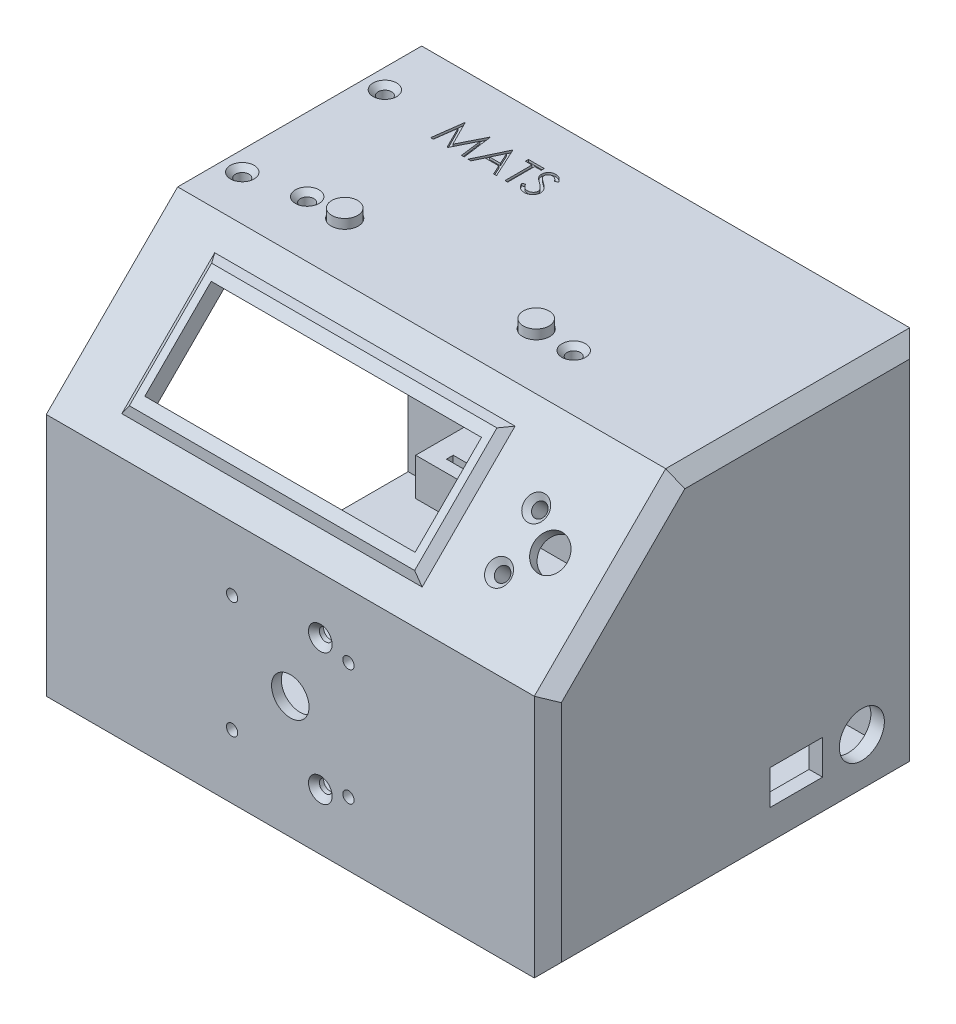
SolidWorks part; units mm, degrees
ref_plane "Front Plane" through (0, 0, 0) normal (0, 0, 1) x (1, 0, 0)
ref_plane "Top Plane" through (0, 0, 0) normal (0, 1, 0) x (1, 0, 0)
ref_plane "Right Plane" through (0, 0, 0) normal (1, 0, 0) x (0, 0, -1)
sketch "Sketch1" plane through (0, 0, 0) normal (0, 0, 1) x (1, 0, 0)
  line L1 (-65, 32.5) -> (65, 32.5)
  line L2 (-65, 32.5) -> (-65, -32.5)
  line L3 (-65, -32.5) -> (65, -32.5)
  line L4 (65, 32.5) -> (65, -32.5)
  line L5 (-65, 32.5) -> (65, -32.5) construction
  line L6 (-65, -32.5) -> (65, 32.5) construction
  point P0 (0, 0)
  dimension "D1" = 130
  dimension "D2" = 65
extrude "Boss-Extrude1" add sketch "Sketch1" against normal blind 3.6 contours L2 L3 L4 L1
sketch "Sketch2" plane through (65, 0, 0) normal (1, 0, 0) x (0, 0, -1)
  line L0 (0, -32.5) -> (100, -32.5)
  line L1 (100, -32.5) -> (100, 67.5)
  line L2 (100, 67.5) -> (35, 67.5)
  line L3 (35, 67.5) -> (0, 32.5)
  line L4 (0, 32.5) -> (0, -32.5)
  dimension "D1" = 135
  dimension "D2" = 65
  dimension "D3" = 100
ref_plane "Plane1" through (0, 16.25, 16.25) normal (0, -0.7071, -0.7071) x (-1, 0, 0)
sketch "Sketch5" plane through (0, 16.25, 16.25) normal (0, -0.7071, -0.7071) x (-1, 0, 0)
  line L1 (65, 22.981) -> (-65, 22.981)
  line L2 (65, 22.981) -> (65, 72.4784)
  line L3 (65, 72.4784) -> (-65, 72.4784)
  line L4 (-65, 22.981) -> (-65, 72.4784)
extrude "Boss-Extrude2" add sketch "Sketch5" along normal blind 2.8
ref_plane "Plane2" through (0, 67.5, 0) normal (0, -1, 0) x (-1, 0, 0)
sketch "Sketch7" plane through (0, 67.5, 0) normal (0, -1, 0) x (-1, 0, 0)
  line L1 (65, 35) -> (-65, 35)
  line L2 (65, 35) -> (65, 100)
  line L3 (65, 100) -> (-65, 100)
  line L4 (-65, 35) -> (-65, 100)
extrude "Boss-Extrude3" add sketch "Sketch7" along normal blind 3.6
ref_plane "Plane3" through (0, -32.5, 0) normal (0, 1, 0) x (1, 0, 0)
ref_plane "Plane4" through (0, 0, -100) normal (0, 0, -1) x (-1, 0, 0)
sketch "Sketch9" plane through (0, -32.5, 0) normal (0, 1, 0) x (1, 0, 0)
  line L1 (65, 0) -> (-65, 0)
  line L2 (65, 0) -> (65, 100)
  line L3 (65, 100) -> (-65, 100)
  line L4 (-65, 0) -> (-65, 100)
  line L6 (65, 100) -> (65, 35) construction
extrude "Boss-Extrude4" add sketch "Sketch9" along normal blind 3.6
sketch "Sketch10" plane through (0, 0, -100) normal (0, 0, -1) x (-1, 0, 0)
  line L1 (-65, 67.5) -> (65, 67.5)
  line L2 (-65, 67.5) -> (-65, -32.5)
  line L3 (-65, -32.5) -> (65, -32.5)
  line L4 (65, 67.5) -> (65, -32.5)
extrude "Boss-Extrude5" add sketch "Sketch10" against normal blind 3.6
extrude "Boss-Extrude6" add sketch "Sketch2" along normal blind 3.6 draft 45
sketch "Sketch11" plane through (0, 16.25, 16.25) normal (0, 0.7071, 0.7071) x (1, 0, 0)
  line L0 (-65, 22.981) -> (-65, 72.4784) construction
  line L1 (-50, 65.2297) -> (30, 65.2297)
  line L2 (-50, 65.2297) -> (-50, 30.2297)
  line L3 (-50, 30.2297) -> (30, 30.2297)
  line L4 (30, 65.2297) -> (30, 30.2297)
  point P4 (-50, 47.7297)
  dimension "D1" = 80
  dimension "D2" = 35
  dimension "D3" = 15
extrude "Boss-Extrude7" add sketch "Sketch11" along normal blind 2 draft 45
sketch "Sketch12" plane through (0, 17.6642, 17.6642) normal (0, 0.7071, 0.7071) x (1, 0, 0)
  line L1 (-46, 35.2297) -> (26, 35.2297)
  line L2 (-46, 35.2297) -> (-46, 60.2297)
  line L3 (-46, 60.2297) -> (26, 60.2297)
  line L4 (26, 35.2297) -> (26, 60.2297)
  line L5 (-46, 35.2297) -> (26, 60.2297) construction
  line L6 (-46, 60.2297) -> (26, 35.2297) construction
  line L7 (28, 63.2297) -> (-48, 32.2297) construction
  point P0 (-10, 47.7297)
  point P9 (-10, 47.7297)
  dimension "D1" = 72
  dimension "D2" = 25
extrude "Cut-Extrude1" cut sketch "Sketch12" against normal up to next
sketch "Sketch13" plane through (65, 0, 0) normal (-1, 0, 0) x (0, 0, 1)
  line L1 (-73.186, -20.9627) -> (-59.186, -20.9627)
  line L2 (-73.186, -20.9627) -> (-73.186, -11.7627)
  line L3 (-73.186, -11.7627) -> (-59.186, -11.7627)
  line L4 (-59.186, -20.9627) -> (-59.186, -11.7627)
  line L5 (-73.186, -20.9627) -> (-59.186, -11.7627) construction
  line L6 (-73.186, -11.7627) -> (-59.186, -20.9627) construction
  circle A0 centre (-83.6497, -16.3627) radius 6
  point P0 (-66.186, -16.3627)
  dimension "D3" = 6
  dimension "D1" = 14
  dimension "D2" = 9.2
extrude "Cut-Extrude2" cut sketch "Sketch13" against normal up to next
sketch "Sketch14" plane through (0, 14.2701, 14.2701) normal (0, -0.7071, -0.7071) x (1, 0, 0)
  line L1 (27, -70.1873) -> (37, -70.1873)
  line L2 (27, -70.1873) -> (27, -25.2721)
  line L3 (27, -25.2721) -> (37, -25.2721)
  line L4 (37, -70.1873) -> (37, -25.2721)
  line L5 (65, -25.2721) -> (-65, -25.2721) construction
  line L6 (26, -35.2297) -> (26, -60.2297) construction
  dimension "D1" = 10
  dimension "D2" = 1
ref_plane "Plane5" through (0, 10.0275, 10.0275) normal (0, -0.7071, -0.7071) x (-1, 0, 0)
sketch "Sketch15" plane through (0, 10.0275, 10.0275) normal (0, -0.7071, -0.7071) x (-1, 0, 0)
  line L0 (-27, 70.1873) -> (-27, 25.2721) construction
  line L1 (-27, 79.3357) -> (-35, 79.3357)
  line L2 (-27, 79.3357) -> (-27, 14.3733)
  line L3 (-27, 14.3733) -> (-35, 14.3733)
  line L4 (-35, 79.3357) -> (-35, 14.3733)
  dimension "D1" = 8
loft "Loft1" add profiles "Sketch15", "Sketch14"
sketch "Sketch16" plane through (27, 0, 0) normal (-1, 0, 0) x (0, 0, 1)
  line L0 (-14.9903, 43.5305) -> (-25.5969, 54.1371)
  line L1 (-3.6, 32.1402) -> (-35.3598, 63.9) construction
  line L2 (-25.5969, 54.1371) -> (-27.1526, 52.5815)
  line L3 (-27.1526, 52.5815) -> (-34.754, 60.1829)
  line L4 (-34.754, 60.1829) -> (-36.1682, 58.7687)
  line L5 (-36.1682, 58.7687) -> (-9.581, 32.1815)
  line L6 (-9.581, 32.1815) -> (-8.1667, 33.5957)
  line L7 (-8.1667, 33.5957) -> (-16.546, 41.9749)
  line L8 (-16.546, 41.9749) -> (-14.9903, 43.5305)
  point P5 (-20.2936, 48.8338)
  dimension "D1" = 37.6
  dimension "D2" = 15
  dimension "D3" = 2.2
  dimension "D4" = 2
extrude "Cut-Extrude3" cut sketch "Sketch16" against normal blind 5
sketch "Sketch17" plane through (0, 0, 0) normal (0, 0, 1) x (1, 0, 0)
  circle A0 centre (0, 0) radius 5
  dimension "D1" = 5
extrude "Cut-Extrude4" cut sketch "Sketch17" against normal up to next
sketch "Sketch18" plane through (0, 0, 0) normal (0, 0, 1) x (1, 0, 0)
  line L0 (8, 17.5) -> (8, -17.5) construction
  point P3 (8, 0)
  dimension "D1" = 8
  dimension "D2" = 35
hole_wizard "CSK for M3 Countersunk Flat Head1" positions "Sketch19" profile "Sketch20" countersink size "M3" standard "BSI"
sketch "Sketch19" plane through (0, 0, 0) normal (0, 0, 1) x (1, 0, 0)
  point P0 (8, 17.5)
  point P3 (8, -17.5)
sketch "Sketch20" plane through (8, 17.5, 0) normal (1, 0, 0) x (0, -1, 0)
  line L0 (0, 0) -> (0, 3.6)
  line L1 (0, 3.6) -> (1.7, 3.6)
  line L2 (1.7, 3.6) -> (1.7, 1.45)
  line L3 (1.7, 1.45) -> (3.15, 0)
  line L5 (3.15, 0) -> (0, 0)
  line L6 (-1.7, 1.45) -> (-3.15, 0) construction
  line L11 (0, -6.35) -> (0, 107.95) construction
  dimension "Thru Hole Dia." = 3.4
  dimension "Thru Hole Depth" = 3.6
  dimension "Near C'Sink Dia." = 6.3
  dimension "Near C'Sink Angle" = 90
sketch "Sketch21" plane through (0, 0, -3.6) normal (0, 0, -1) x (-1, 0, 0)
  line L0 (-8, 17.5) -> (-8, -17.5) construction
  line L1 (-8, 17.5) -> (-8, -17.5) construction
  line L2 (-4.1758, -13.6234) -> (-4.25, -17.5)
  line L3 (-11.75, 17.5) -> (-11.7477, 13.6447)
  line L4 (-4.25, 17.5) -> (-4.25, 13.644)
  line L5 (-11.75, -17.5) -> (-11.75, -13.644)
  line L6 (-20.8149, 6) -> (-26, 6)
  line L7 (-26, 6) -> (-26, -6)
  line L8 (-26, -6) -> (-20.8149, -6)
  arc A0 (-11.7477, 13.6447) -> (-20.8149, 6) centre (-8, 0) ccw
  arc A1 (-4.25, 17.5) -> (-11.75, 17.5) centre (-8, 17.5) ccw
  arc A2 (-11.75, -17.5) -> (-4.25, -17.5) centre (-8, -17.5) ccw
  arc A3 (-4.1758, -13.6234) -> (-4.25, 13.644) centre (-8, 0) ccw
  arc A4 (-20.8149, -6) -> (-11.75, -13.644) centre (-8, 0) ccw
  point P8 (-8, 0)
  point P17 (-26, 0)
  dimension "D1" = 14.15
  dimension "D2" = 12
  dimension "D3" = 18
sketch "Sketch22" plane through (65, 0, 0) normal (-1, 0, 0) x (0, 0, 1)
  line L0 (-63.6165, 21.8931) -> (-63.6165, -4.6069) construction
  line L1 (-63.6165, -4.6069) -> (-34.1165, -4.6069) construction
  line L2 (-34.1165, -4.6069) -> (-34.1165, 21.8931) construction
  line L3 (-34.1165, 21.8931) -> (-63.6165, 21.8931) construction
  line L5 (-68.6165, 26.8931) -> (-58.6165, 26.8931)
  line L6 (-68.6165, 26.8931) -> (-68.6165, 16.8931)
  line L7 (-68.6165, 16.8931) -> (-58.6165, 16.8931)
  line L8 (-58.6165, 26.8931) -> (-58.6165, 16.8931)
  line L9 (-68.6165, 26.8931) -> (-58.6165, 16.8931) construction
  line L10 (-68.6165, 16.8931) -> (-58.6165, 26.8931) construction
  line L11 (-39.1165, 26.8931) -> (-29.1165, 26.8931)
  line L12 (-39.1165, 26.8931) -> (-39.1165, 16.8931)
  line L13 (-39.1165, 16.8931) -> (-29.1165, 16.8931)
  line L14 (-29.1165, 26.8931) -> (-29.1165, 16.8931)
  line L15 (-39.1165, 26.8931) -> (-29.1165, 16.8931) construction
  line L16 (-39.1165, 16.8931) -> (-29.1165, 26.8931) construction
  line L17 (-68.6165, -9.6069) -> (-58.6165, -9.6069)
  line L18 (-68.6165, -9.6069) -> (-68.6165, 0.3931)
  line L19 (-68.6165, 0.3931) -> (-58.6165, 0.3931)
  line L20 (-58.6165, -9.6069) -> (-58.6165, 0.3931)
  line L21 (-68.6165, -9.6069) -> (-58.6165, 0.3931) construction
  line L22 (-68.6165, 0.3931) -> (-58.6165, -9.6069) construction
  line L23 (-39.1165, 0.3931) -> (-29.1165, 0.3931)
  line L24 (-39.1165, 0.3931) -> (-39.1165, -9.6069)
  line L25 (-39.1165, -9.6069) -> (-29.1165, -9.6069)
  line L26 (-29.1165, 0.3931) -> (-29.1165, -9.6069)
  line L27 (-39.1165, 0.3931) -> (-29.1165, -9.6069) construction
  line L28 (-39.1165, -9.6069) -> (-29.1165, 0.3931) construction
  dimension "D1" = 29.5
  dimension "D2" = 26.5
  dimension "D3" = 10
extrude "Boss-Extrude8" add sketch "Sketch22" along normal blind 8
sketch "Sketch23" plane through (65, 0, 0) normal (-1, 0, 0) x (0, 0, 1)
  line L0 (-66.6165, 26.8931) -> (-66.6165, 20.4251)
  line L1 (-66.6165, 20.4251) -> (-63.6165, 18.6931)
  line L2 (-63.6165, 21.8931) -> (-63.6165, -4.6069) construction
  line L3 (-63.6165, 18.6931) -> (-60.6165, 20.4251)
  line L4 (-39.1165, 0.3931) -> (-29.1165, 0.3931) construction
  line L5 (-60.6165, 20.4251) -> (-60.6165, 26.8931)
  line L6 (-60.6165, 26.8931) -> (-66.6165, 26.8931)
  line L7 (-68.6165, 0.3931) -> (-58.6165, 0.3931) construction
  line L8 (-68.6165, 26.8931) -> (-58.6165, 26.8931) construction
  line L9 (-34.1165, -4.6069) -> (-34.1165, 21.8931) construction
  line L10 (-37.1165, 26.8931) -> (-37.1165, 20.4251)
  line L11 (-37.1165, 20.4251) -> (-34.1165, 18.6931)
  line L12 (-34.1165, 18.6931) -> (-31.1165, 20.4251)
  line L13 (-31.1165, 20.4251) -> (-31.1165, 26.8931)
  line L14 (-31.1165, 26.8931) -> (-37.1165, 26.8931)
  line L15 (-66.6165, 0.3931) -> (-66.6165, -6.0749)
  line L16 (-66.6165, -6.0749) -> (-63.6165, -7.8069)
  line L17 (-63.6165, -7.8069) -> (-60.6165, -6.0749)
  line L18 (-60.6165, -6.0749) -> (-60.6165, 0.3931)
  line L19 (-60.6165, 0.3931) -> (-66.6165, 0.3931)
  line L20 (-37.1165, 0.3931) -> (-37.1165, -6.0749)
  line L21 (-37.1165, -6.0749) -> (-34.1165, -7.8069)
  line L22 (-34.1165, -7.8069) -> (-31.1165, -6.0749)
  line L23 (-31.1165, -6.0749) -> (-31.1165, 0.3931)
  line L24 (-31.1165, 0.3931) -> (-37.1165, 0.3931)
  line L25 (-39.1165, 26.8931) -> (-29.1165, 26.8931) construction
  dimension "D1" = 6
  dimension "D2" = 120
  dimension "D3" = 120
  dimension "D4" = 8.2
  dimension "D5" = 6
  dimension "D6" = 120
  dimension "D7" = 120
  dimension "D8" = 6
  dimension "D9" = 120
  dimension "D10" = 120
  dimension "D11" = 6
  dimension "D12" = 120
  dimension "D13" = 120
  dimension "D14" = 8.2
  dimension "D15" = 8.2
  dimension "D16" = 10
  dimension "D17" = 10
  dimension "D18" = 8.2
extrude "Cut-Extrude5" cut sketch "Sketch23" along normal blind 3
hole_wizard "Ø3.0mm Dowel Hole1" positions "Sketch24" profile "Sketch26" hole size "Ø3.0" standard "BSI"
sketch "Sketch24" plane through (57, 0, 0) normal (-1, 0, 0) x (0, 0, 1)
  point P0 (-63.6165, 21.8931)
  point P3 (-34.1165, 21.8931)
  point P6 (-63.6165, -4.6069)
  point P9 (-34.1165, -4.6069)
sketch "Sketch26" plane through (57, 21.8931, -63.6165) normal (0, 1, 0) x (0, 0, 1)
  line L0 (0, 0) -> (0, 8.9003)
  line L1 (0, 8.9003) -> (1.5, 7.999)
  line L2 (1.5, 7.999) -> (1.5, 0)
  line L5 (1.5, 0) -> (0, 0)
  line L10 (0, 8.9003) -> (-1.5, 7.999) construction
  line L11 (0, -6.35) -> (0, 107.95) construction
  dimension "Hole Dia." = 3
  dimension "Hole Depth" = 7.999
  dimension "Drill Angle" = 118
sketch "Sketch27" plane through (0, 0, -96.4) normal (0, 0, 1) x (1, 0, 0)
  line L0 (-45, 53.9) -> (35, 53.9) construction
  line L1 (35, 53.9) -> (35, -16.1) construction
  line L2 (35, -16.1) -> (-45, -16.1) construction
  line L3 (-45, -16.1) -> (-45, 53.9) construction
  line L4 (-65, -28.9) -> (-65, 63.9) construction
  line L5 (-65, 63.9) -> (65, 63.9) construction
  line L7 (-50, -11.1) -> (-30, -11.1)
  line L8 (-50, -11.1) -> (-50, -21.1)
  line L9 (-50, -21.1) -> (-30, -21.1)
  line L10 (-30, -11.1) -> (-30, -21.1)
  line L11 (-50, -11.1) -> (-30, -21.1) construction
  line L12 (-50, -21.1) -> (-30, -11.1) construction
  line L13 (20, -11.1) -> (40, -11.1)
  line L14 (20, -11.1) -> (20, -21.1)
  line L15 (20, -21.1) -> (40, -21.1)
  line L16 (40, -11.1) -> (40, -21.1)
  line L17 (20, -11.1) -> (40, -21.1) construction
  line L18 (20, -21.1) -> (40, -11.1) construction
  point P8 (-40, -16.1)
  point P13 (30, -16.1)
  dimension "D1" = 80
  dimension "D2" = 70
  dimension "D3" = 20
  dimension "D4" = 10
  dimension "D5" = 5
  dimension "D6" = 10
  dimension "D7" = 20
  dimension "D8" = 5
  dimension "D9" = 10
  dimension "D10" = 20
extrude "Boss-Extrude9" add sketch "Sketch27" along normal blind 13
sketch "Sketch28" plane through (0, -11.1, 0) normal (0, 1, 0) x (1, 0, 0)
  line L1 (-30, 88.4) -> (-45, 88.4)
  line L2 (-30, 88.4) -> (-30, 86.5985)
  line L3 (-30, 86.5985) -> (-45, 86.5985)
  line L4 (-45, 88.4) -> (-45, 86.5985)
  line L6 (20, 88.4) -> (35, 88.4)
  line L7 (20, 88.4) -> (20, 86.5985)
  line L8 (20, 86.5985) -> (35, 86.5985)
  line L9 (35, 88.4) -> (35, 86.5985)
  line L11 (-50, 96.4) -> (-30, 96.4) construction
  dimension "D1" = 15
  dimension "D2" = 1.8015
  dimension "D3" = 8
extrude "Cut-Extrude12" cut sketch "Sketch28" against normal blind 5
sketch "Sketch29" plane through (0, 0, -96.4) normal (0, 0, 1) x (1, 0, 0)
  line L0 (-45, -16.1) -> (-45, 53.9) construction
  line L1 (35, 53.9) -> (35, -16.1) construction
  line L2 (-45, 53.9) -> (35, 53.9) construction
  line L3 (-30, 48.9) -> (-30, 32.8454) construction
  line L4 (1, 48.9) -> (-30, 48.9) construction
  line L5 (-35, 53.9) -> (-25, 53.9)
  line L6 (-35, 53.9) -> (-35, 43.9)
  line L7 (-35, 43.9) -> (-25, 43.9)
  line L8 (-25, 53.9) -> (-25, 43.9)
  line L9 (-35, 53.9) -> (-25, 43.9) construction
  line L10 (-35, 43.9) -> (-25, 53.9) construction
  line L11 (20, 48.9) -> (20, 33.3075) construction
  line L12 (51, 48.9) -> (20, 48.9) construction
  line L13 (15, 53.9) -> (25, 53.9)
  line L14 (15, 53.9) -> (15, 43.9)
  line L15 (15, 43.9) -> (25, 43.9)
  line L16 (25, 53.9) -> (25, 43.9)
  line L17 (15, 53.9) -> (25, 43.9) construction
  line L18 (15, 43.9) -> (25, 53.9) construction
  point P0 (-30, 48.9)
  point P1 (20, 48.9)
  dimension "D1" = 15
  dimension "15" = 15
  dimension "D2" = 5
  dimension "D3" = 31
  dimension "D4" = 10
  dimension "D5" = 31
  dimension "D6" = 10
extrude "Boss-Extrude10" add sketch "Sketch29" along normal blind 8
ref_plane "Plane6" through (0, 0, -94.4) normal (0, 0, 1) x (1, 0, 0)
sketch "Sketch31" plane through (0, 0, -94.4) normal (0, 0, 1) x (1, 0, 0)
  line L0 (-33, 53.9) -> (-33, 47.432)
  line L1 (-33, 47.432) -> (-30, 45.6999)
  line L2 (-30, 45.6999) -> (-27, 47.432)
  line L3 (-27, 47.432) -> (-27, 53.9)
  line L4 (-27, 53.9) -> (-33, 53.9)
  line L5 (-35, 53.9) -> (-25, 53.9) construction
  line L6 (-30, 48.9) -> (-30, 32.8454) construction
  line L7 (17, 53.9) -> (17, 47.4321)
  line L8 (17, 47.4321) -> (20, 45.7)
  line L9 (20, 45.7) -> (23, 47.4321)
  line L10 (23, 47.4321) -> (23, 53.9)
  line L11 (23, 53.9) -> (17, 53.9)
  line L12 (20, 48.9) -> (20, 33.3075) construction
  line L13 (15, 53.9) -> (25, 53.9) construction
  dimension "D1" = 6
  dimension "D2" = 120
  dimension "D3" = 120
  dimension "D4" = 3.2001
  dimension "D5" = 6
  dimension "D6" = 120
  dimension "D7" = 120
  dimension "D8" = 3.2
extrude "Cut-Extrude7" cut sketch "Sketch31" along normal blind 3
hole_wizard "Ø5.0mm Dowel Hole1" positions "Sketch34" profile "Sketch33" hole size "Ø5.0" standard "BSI"
sketch "Sketch34" plane through (0, 0, -88.4) normal (0, 0, 1) x (1, 0, 0)
  point P0 (-30, 48.9)
  point P3 (20, 48.9)
sketch "Sketch33" plane through (-30, 48.9, -88.4) normal (1, 0, 0) x (0, -1, 0)
  line L0 (0, 0) -> (0, 10.5022)
  line L1 (0, 10.5022) -> (2.5, 9)
  line L2 (2.5, 9) -> (2.5, 0)
  line L5 (2.5, 0) -> (0, 0)
  line L10 (0, 10.5022) -> (-2.5, 9) construction
  line L11 (0, -6.35) -> (0, 107.95) construction
  dimension "Hole Dia." = 5
  dimension "Hole Depth" = 9
  dimension "Drill Angle" = 118
sketch "Sketch35" plane through (0, 0, 0) normal (0, 0, 1) x (1, 0, 0)
  line L0 (-15.5, 15.5) -> (15.5, -15.5) construction
  line L1 (15.5, 15.5) -> (-15.5, -15.5) construction
  point P2 (0, 0)
  point P7 (0, 0)
  dimension "D1" = 31
hole_wizard "Ø3.0mm Dowel Hole3" positions "Sketch36" profile "Sketch38" hole size "Ø3.0" standard "BSI" end condition up to next
sketch "Sketch36" plane through (0, 0, 0) normal (0, 0, 1) x (1, 0, 0)
  point P0 (-15.5, 15.5)
  point P3 (15.5, 15.5)
  point P6 (15.5, -15.5)
  point P9 (-15.5, -15.5)
sketch "Sketch38" plane through (-15.5, 15.5, 0) normal (1, 0, 0) x (0, -1, 0)
  line L0 (0, 0) -> (0, 3.6)
  line L1 (0, 3.6) -> (1.5, 3.6)
  line L2 (1.5, 3.6) -> (1.5, 0)
  line L5 (1.5, 0) -> (0, 0)
  line L11 (0, -6.35) -> (0, 107.95) construction
  dimension "Thru Hole Dia." = 3
  dimension "Thru Hole Depth" = 3.6
sketch "Sketch39" plane through (0, 0, -3.6) normal (0, 0, -1) x (-1, 0, 0)
  line L1 (-12.5004, 13.7673) -> (-12.4996, 17.2314)
  line L2 (-12.4996, 17.2314) -> (-15.4993, 18.9641)
  line L3 (-15.4993, 18.9641) -> (-18.4996, 17.2327)
  line L4 (-18.4996, 17.2327) -> (-18.5004, 13.7686)
  line L5 (-18.5004, 13.7686) -> (-15.5007, 12.0359)
  line L6 (-15.5007, 12.0359) -> (-12.5004, 13.7673)
  line L12 (18.6392, 13.9759) -> (18.6399, 17.44)
  line L13 (18.6399, 17.44) -> (15.6402, 19.1727)
  line L14 (15.6402, 19.1727) -> (12.6399, 17.4413)
  line L15 (12.6399, 17.4413) -> (12.6392, 13.9771)
  line L16 (12.6392, 13.9771) -> (15.6388, 12.2445)
  line L17 (15.6388, 12.2445) -> (18.6392, 13.9759)
  line L18 (-12.7838, -16.9883) -> (-12.7831, -13.5242)
  line L19 (-12.7831, -13.5242) -> (-15.7827, -11.7915)
  line L20 (-15.7827, -11.7915) -> (-18.7831, -13.523)
  line L21 (-18.7831, -13.523) -> (-18.7838, -16.9871)
  line L22 (-18.7838, -16.9871) -> (-15.7841, -18.7197)
  line L23 (-15.7841, -18.7197) -> (-12.7838, -16.9883)
  line L24 (18.62, -16.9023) -> (18.6207, -13.4382)
  line L25 (18.6207, -13.4382) -> (15.621, -11.7055)
  line L26 (15.621, -11.7055) -> (12.6207, -13.4369)
  line L27 (12.6207, -13.4369) -> (12.62, -16.901)
  line L28 (12.62, -16.901) -> (15.6196, -18.6337)
  line L29 (15.6196, -18.6337) -> (18.62, -16.9023)
  circle A0 centre (-15.5, 15.5) radius 3 construction
  circle A1 centre (15.6395, 15.7086) radius 3 construction
  circle A2 centre (-15.7834, -15.2556) radius 3 construction
  circle A3 centre (15.6203, -15.1696) radius 3 construction
extrude "Cut-Extrude8" cut sketch "Sketch39" against normal blind 1.5
hole_wizard "CSK for M3 Countersunk Flat Head4" positions "Sketch48" profile "Sketch49" countersink size "M3" standard "BSI" end condition up to next
sketch "Sketch48" plane through (0, -32.5, 0) normal (0, -1, 0) x (-1, 0, 0)
  point P0 (59.8, 25)
  point P2 (59.8, 75)
sketch "Sketch49" plane through (-59.8, -32.5, -25) normal (1, 0, 0) x (0, 0, -1)
  line L0 (0, 0) -> (0, 3.6)
  line L1 (0, 3.6) -> (1.8, 3.6)
  line L2 (1.8, 3.6) -> (1.8, 1.35)
  line L3 (1.8, 1.35) -> (3.15, 0)
  line L5 (3.15, 0) -> (0, 0)
  line L6 (-1.8, 1.35) -> (-3.15, 0) construction
  line L11 (0, -6.35) -> (0, 107.95) construction
  dimension "Thru Hole Dia." = 3.6
  dimension "Thru Hole Depth" = 3.6
  dimension "Near C'Sink Dia." = 6.3
  dimension "Near C'Sink Angle" = 90
hole_wizard "CSK for M3 Countersunk Flat Head5" positions "Sketch52" profile "Sketch54" countersink size "M3" standard "BSI" end condition up to next
sketch "Sketch52" plane through (0, 67.5, 0) normal (0, 1, 0) x (1, 0, 0)
  line L0 (-65, 35) -> (65, 35) construction
  line L1 (-65, 35) -> (-65, 100) construction
  line L2 (-65, 100) -> (65, 100) construction
  point P0 (-59.8, 85)
  point P2 (-59.8, 47)
  dimension "D1" = 12
  dimension "D2" = 5.2
  dimension "D3" = 15
  dimension "D4" = 5.2
sketch "Sketch54" plane through (-59.8, 67.5, -85) normal (1, 0, 0) x (0, 0, 1)
  line L0 (0, 0) -> (0, 3.6)
  line L1 (0, 3.6) -> (1.8, 3.6)
  line L2 (1.8, 3.6) -> (1.8, 1.35)
  line L3 (1.8, 1.35) -> (3.15, 0)
  line L5 (3.15, 0) -> (0, 0)
  line L6 (-1.8, 1.35) -> (-3.15, 0) construction
  line L11 (0, -6.35) -> (0, 107.95) construction
  dimension "Thru Hole Dia." = 3.6
  dimension "Thru Hole Depth" = 3.6
  dimension "Near C'Sink Dia." = 6.3
  dimension "Near C'Sink Angle" = 90
sketch "Sketch55" plane through (0, 63.9, 0) normal (0, -1, 0) x (1, 0, 0)
  line L0 (-35.5, -50) -> (15.5, -50) construction
  line L4 (-65, -35) -> (65, -35) construction
  line L6 (-42.5, -42) -> (22.5, -42)
  line L7 (-42.5, -42) -> (-42.5, -62)
  line L8 (-42.5, -62) -> (22.5, -62)
  line L9 (22.5, -42) -> (22.5, -62)
  point P4 (-10, -50)
  point P10 (-10, -62)
  dimension "D1" = 51
  dimension "D2" = 15
  dimension "D3" = 8
  dimension "D4" = 20
  dimension "D5" = 65
extrude "Cut-Extrude9" cut sketch "Sketch55" against normal blind 2.5
sketch "Sketch56" plane through (0, 66.4, 0) normal (0, -1, 0) x (1, 0, 0)
  line L1 (-41.8, -43.7) -> (-29.2, -43.7)
  line L2 (-41.8, -43.7) -> (-41.8, -56.3)
  line L3 (-41.8, -56.3) -> (-29.2, -56.3)
  line L4 (-29.2, -43.7) -> (-29.2, -56.3)
  line L5 (-41.8, -43.7) -> (-29.2, -56.3) construction
  line L6 (-41.8, -56.3) -> (-29.2, -43.7) construction
  line L7 (9.2, -43.7) -> (21.8, -43.7)
  line L8 (9.2, -43.7) -> (9.2, -56.3)
  line L9 (9.2, -56.3) -> (21.8, -56.3)
  line L10 (21.8, -43.7) -> (21.8, -56.3)
  line L11 (9.2, -43.7) -> (21.8, -56.3) construction
  line L12 (9.2, -56.3) -> (21.8, -43.7) construction
  point P0 (-35.5, -50)
  point P5 (15.5, -50)
  dimension "D1" = 12.6
sketch "Sketch59" plane through (0, 67.5, 0) normal (0, 1, 0) x (1, 0, 0)
  circle A0 centre (-35.5, 50) radius 3.6
  circle A1 centre (15.5, 50) radius 3.6
  dimension "D2" = 3.6
extrude "Cut-Extrude11" cut sketch "Sketch59" against normal up to next (1.1 mm away)
sketch "Sketch60" plane through (0, 67.5, 0) normal (0, 1, 0) x (1, 0, 0)
  circle A0 centre (-45.5, 50) radius 2.5
  circle A1 centre (25.5, 50) radius 2.5
  dimension "D1" = 2.5
  dimension "D2" = 10
  dimension "D3" = 10
extrude "Boss-Extrude12" add sketch "Sketch60" against normal blind 4.6
hole_wizard "CSK for M3 Countersunk Flat Head7" positions "Sketch63" profile "Sketch64" countersink size "M3" standard "BSI" end condition up to next
sketch "Sketch63" plane through (0, 67.5, 0) normal (0, 1, 0) x (1, 0, 0)
  point P0 (-45.5, 50)
  point P3 (25.5, 50)
sketch "Sketch64" plane through (-45.5, 67.5, -50) normal (1, 0, 0) x (0, 0, 1)
  line L0 (0, 0) -> (0, 4.6)
  line L1 (0, 4.6) -> (1.8, 4.6)
  line L2 (1.8, 4.6) -> (1.8, 1.35)
  line L3 (1.8, 1.35) -> (3.15, 0)
  line L5 (3.15, 0) -> (0, 0)
  line L6 (-1.8, 1.35) -> (-3.15, 0) construction
  line L11 (0, -6.35) -> (0, 107.95) construction
  dimension "Thru Hole Dia." = 3.6
  dimension "Thru Hole Depth" = 4.6
  dimension "Near C'Sink Dia." = 6.3
  dimension "Near C'Sink Angle" = 90
extrude "Cut-Extrude13" cut sketch "Sketch21" against normal blind 1
sketch "Sketch67" plane through (0, 14.2701, 14.2701) normal (0, -0.7071, -0.7071) x (1, 0, 0)
  circle A0 centre (51.6631, -47.8723) radius 4.5
  dimension "D1" = 4.5
extrude "Cut-Extrude14" cut sketch "Sketch67" against normal blind 10
sketch "Sketch68" plane through (0, 14.2701, 14.2701) normal (0, -0.7071, -0.7071) x (1, 0, 0)
  circle A0 centre (43.6631, -53.8723) radius 2.5
  circle A1 centre (43.6631, -39.8723) radius 2.5
  dimension "D1" = 2.5
  dimension "D2" = 2.5
  dimension "D4" = 6
  dimension "D3" = 14
  dimension "D5" = 8
extrude "Boss-Extrude15" add sketch "Sketch68" along normal blind 6.2
sketch "Sketch73" plane through (0, 67.5, 0) normal (0, 1, 0) x (1, 0, 0)
  text T0 "MATS" font "Century Gothic" height 8
extrude "Cut-Extrude15" cut sketch "Sketch73" against normal blind 0.6
hole_wizard "CSK for M3 Countersunk Flat Head8" positions "Sketch77" profile "Sketch79" countersink size "M3" standard "BSI" end condition up to next
sketch "Sketch77" plane through (0, 16.25, 16.25) normal (0, 0.7071, 0.7071) x (1, 0, 0)
  point P0 (43.6631, 53.8723)
  point P3 (43.6631, 39.8723)
sketch "Sketch79" plane through (43.6631, 54.3434, -21.8434) normal (1, 0, 0) x (0, -0.7071, 0.7071)
  line L0 (0, 0) -> (0, 11.5014)
  line L1 (0, 11.5014) -> (1.8, 11.5014)
  line L2 (1.8, 11.5014) -> (1.8, 1.35)
  line L3 (1.8, 1.35) -> (3.15, 0)
  line L5 (3.15, 0) -> (0, 0)
  line L6 (-1.8, 1.35) -> (-3.15, 0) construction
  line L11 (0, -6.35) -> (0, 107.95) construction
  dimension "Thru Hole Dia." = 3.6
  dimension "Thru Hole Depth" = 11.5014
  dimension "Near C'Sink Dia." = 6.3
  dimension "Near C'Sink Angle" = 90
sketch "Sketch80" plane through (0, 66.4, 0) normal (0, -1, 0) x (1, 0, 0)
  circle A0 centre (15.5, -50) radius 3.45
  circle A1 centre (-35.5, -50) radius 3.45
  dimension "D1" = 3.45
  dimension "D2" = 3.45
extrude "Boss-Extrude16" add sketch "Sketch80" against normal blind 3.5 separate body
